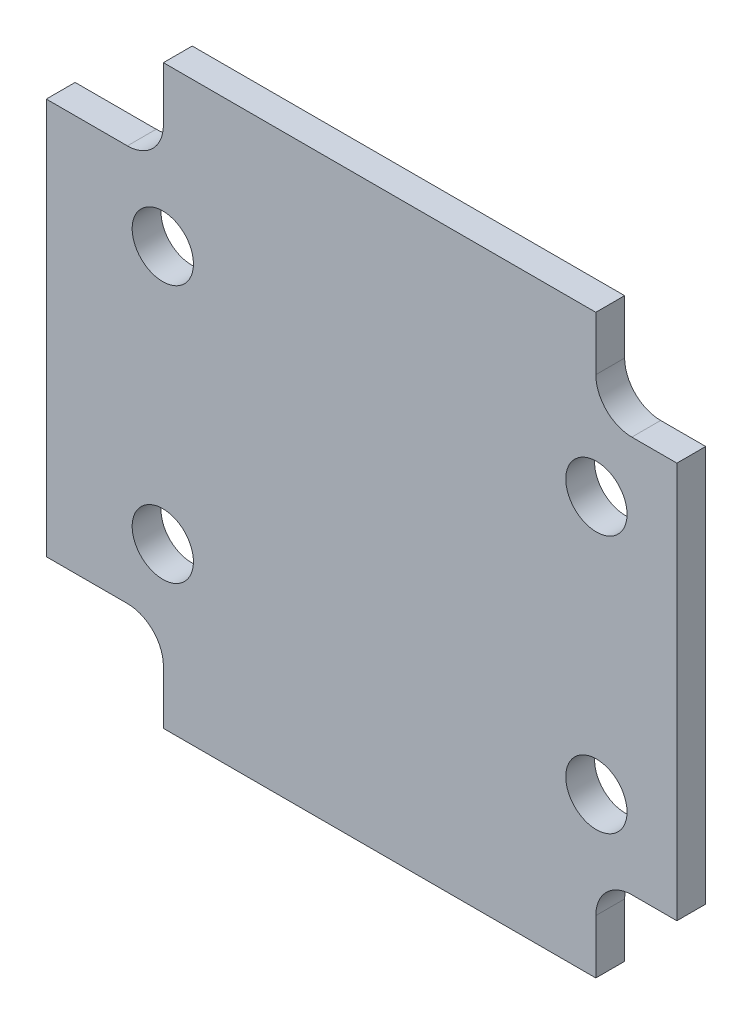
SolidWorks part; units mm, degrees
ref_plane "Спереди" through (0, 0, 0) normal (0, 0, 1) x (1, 0, 0)
ref_plane "Сверху" through (0, 0, 0) normal (0, 1, 0) x (1, 0, 0)
ref_plane "Справа" through (0, 0, 0) normal (1, 0, 0) x (0, 0, -1)
sketch "Эскиз1" plane through (0, 0, 0) normal (0, 0, 1) x (1, 0, 0)
  line L1 (-18.5, 16) -> (18.5, 16)
  line L2 (-18.5, 16) -> (-18.5, -16)
  line L3 (-18.5, -16) -> (18.5, -16)
  line L4 (18.5, 16) -> (18.5, -16)
  line L5 (-18.5, 16) -> (18.5, -16) construction
  line L6 (-18.5, -16) -> (18.5, 16) construction
  point P0 (0, 0)
  dimension "D1" = 37
  dimension "D2" = 32
extrude "Бобышка-Вытянуть1" add sketch "Эскиз1" along normal blind 1.6
sketch "Эскиз2" plane through (0, 0, 1.6) normal (0, 0, 1) x (1, 0, 0)
  line L0 (0, 23.5114) -> (0, -4.2901) construction
  line L1 (-18.5, 16) -> (-12, 16)
  line L2 (-18.5, 16) -> (-18.5, 11)
  line L3 (-18.5, 11) -> (-12, 11)
  line L4 (-12, 16) -> (-12, 11)
  line L5 (21.4906, 0) -> (-21.1925, 0) construction
  line L6 (12, 16) -> (12, 11)
  line L7 (18.5, 11) -> (12, 11)
  line L8 (18.5, 16) -> (18.5, 11)
  line L9 (18.5, 16) -> (12, 16)
  line L10 (18.5, -16) -> (12, -16)
  line L11 (18.5, -16) -> (18.5, -11)
  line L12 (18.5, -11) -> (12, -11)
  line L13 (12, -16) -> (12, -11)
  line L14 (-12, -16) -> (-12, -11)
  line L15 (-18.5, -11) -> (-12, -11)
  line L16 (-18.5, -16) -> (-18.5, -11)
  line L17 (-18.5, -16) -> (-12, -16)
  dimension "D1" = 5
  dimension "D2" = 12
extrude "Вырез-Вытянуть1" cut sketch "Эскиз2" against normal through all
fillet "Скругление1" radius 2 4 edges at (12, 11, 0.8) (-12, 11, 0.8) (-12, -11, 0.8) (12, -11, 0.8)
sketch "Эскиз3" plane through (0, 0, 1.6) normal (0, 0, 1) x (1, 0, 0)
  line L0 (18.5, 11) -> (-18.5, -11) construction
  line L1 (-18.5, 11) -> (18.5, -11) construction
  line L2 (-18.5, 11) -> (-14, 11) construction
  circle A0 centre (0, 0) radius 14 construction
  dimension "D1" = 28
hole_wizard "Отверстие с зазором M31" positions "Эскиз5" profile "Эскиз4" hole size "M3" standard "Ansi Metric"
sketch "Эскиз5" plane through (0, 0, 1.6) normal (0, 0, 1) x (1, 0, 0)
  line L0 (-18.5, 11) -> (18.5, -11) construction
  line L1 (18.5, 11) -> (-18.5, -11) construction
  circle A0 centre (0, 0) radius 14 construction
  point P0 (-12.0335, 7.1551)
  point P6 (12.0335, 7.1551)
  point P10 (12.0335, -7.1551)
  point P12 (-12.0335, -7.1551)
sketch "Эскиз4" plane through (-12.0335, 7.1551, 1.6) normal (1, 0, 0) x (0, -1, 0)
  line L0 (0, 0) -> (0, 19.0215)
  line L1 (0, 19.0215) -> (1.7, 18)
  line L2 (1.7, 18) -> (1.7, 0)
  line L5 (1.7, 0) -> (0, 0)
  line L10 (0, 19.0215) -> (-1.7, 18) construction
  line L11 (0, -6.35) -> (0, 107.95) construction
  dimension "Диаметр отверстия" = 3.4
  dimension "Глубина отверстия" = 18
  dimension "Угол заточки сверла" = 118
ref_plane "Плоскость1" through (0, 0, 0) normal (0, -1, 0) x (-1, 0, 0)
ref_plane "Плоскость2" through (0, 0, 0) normal (-1, 0, 0) x (0, 0, 1)
sketch "Эскиз7" plane through (18.5, 0, 0) normal (1, 0, 0) x (0, 0, -1)
  line L0 (-0.8, 11) -> (-0.8, -11) construction
  line L1 (0, 11) -> (-1.6, 11) construction
  line L2 (0, -11) -> (-1.6, -11) construction
  line L3 (0, -13) -> (0, -11) construction
  line L4 (-1.6, 12.4258) -> (0, 12.4258)
  line L5 (-1.6, 12.4258) -> (-1.6, -12.4258)
  line L6 (-1.6, -12.4258) -> (0, -12.4258)
  line L7 (0, 12.4258) -> (0, -12.4258)
  line L8 (-1.6, 12.4258) -> (0, -12.4258) construction
  line L9 (-1.6, -12.4258) -> (0, 12.4258) construction
  point P6 (-0.8, 0)
extrude "Вырез-Вытянуть2" cut sketch "Эскиз7" against normal blind 2
